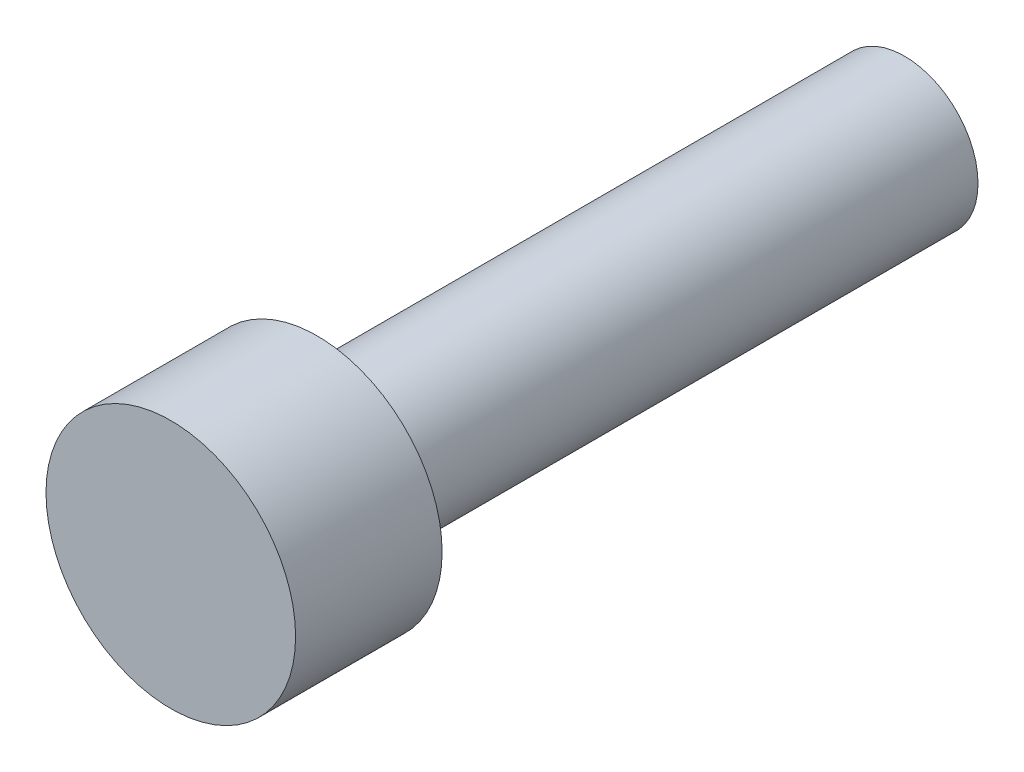
SolidWorks part; units mm, degrees
ref_plane "前视基准面" through (0, 0, 0) normal (0, 0, 1) x (1, 0, 0)
ref_plane "上视基准面" through (0, 0, 0) normal (0, 1, 0) x (1, 0, 0)
ref_plane "右视基准面" through (0, 0, 0) normal (1, 0, 0) x (0, 0, -1)
other "Configuration Table"
sketch "草图1" plane through (0, 0, 0) normal (0, 0, 1) x (1, 0, 0)
  circle A0 centre (0, 0) radius 2.5
extrude "凸台-拉伸1" add sketch "草图1" against normal blind 20
sketch "草图2" plane through (0, 0, 0) normal (0, 0, 1) x (1, 0, 0)
  circle A0 centre (0, 0) radius 4.25
extrude "凸台-拉伸2" add sketch "草图2" along normal blind 4.99
